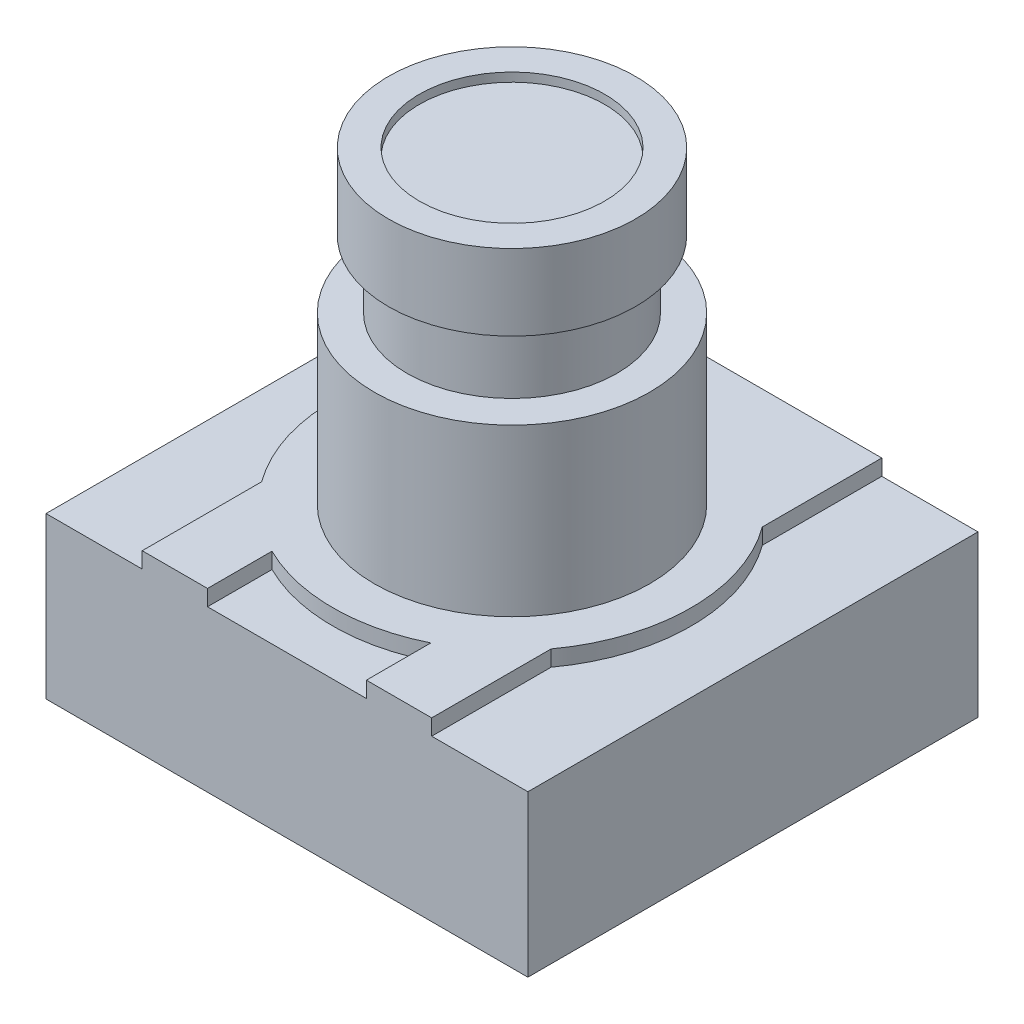
SolidWorks part; units mm, degrees
ref_plane "Front Plane" through (0, 0, 0) normal (0, 0, 1) x (1, 0, 0)
ref_plane "Top Plane" through (0, 0, 0) normal (0, 1, 0) x (1, 0, 0)
ref_plane "Right Plane" through (0, 0, 0) normal (1, 0, 0) x (0, 0, -1)
sketch "Sketch1" plane through (0, 0, 0) normal (0, 1, 0) x (1, 0, 0)
  line L1 (-13.65, 12.75) -> (13.65, 12.75)
  line L2 (-13.65, 12.75) -> (-13.65, -12.75)
  line L3 (-13.65, -12.75) -> (13.65, -12.75)
  line L4 (13.65, 12.75) -> (13.65, -12.75)
  line L5 (-13.65, 12.75) -> (13.65, -12.75) construction
  line L6 (-13.65, -12.75) -> (13.65, 12.75) construction
  point P0 (0, 0)
  dimension "D1" = 27.3
  dimension "D2" = 25.5
extrude "Boss-Extrude1" add sketch "Sketch1" along normal blind 10
sketch "Sketch2" plane through (0, 10, 0) normal (0, 1, 0) x (1, 0, 0)
  line L0 (-8.2, 12.75) -> (-8.2, -12.75)
  line L1 (13.65, 12.75) -> (-13.65, 12.75) construction
  line L2 (-13.65, -12.75) -> (13.65, -12.75) construction
  line L3 (0, 12.75) -> (0, -12.75) construction
  line L4 (8.2, 12.75) -> (8.2, -12.75)
  line L5 (-4.5, -9.0979) -> (-4.5, -12.75)
  line L6 (4.5, -9.0979) -> (4.5, -12.75)
  circle A0 centre (0, 0) radius 10.15
  line M1 (13.65, -12.75) -> (13.65, 12.75)
  line M2 (13.65, 12.75) -> (-13.65, 12.75)
  line M3 (-13.65, 12.75) -> (-13.65, -12.75)
  line M4 (-13.65, -12.75) -> (13.65, -12.75)
  dimension "D1" = 20.3
  dimension "D2" = 16.4
  dimension "D3" = 9
extrude "Cut-Extrude1" cut sketch "Sketch2" against normal blind 0.9 contours A0 L0 M2 M3 M4 | A0 L4 M4 M1 M2 | L3 A0 L5 M4 | A0 L3 L6 M4
sketch "Sketch3" plane through (0, 10, 0) normal (0, 1, 0) x (1, 0, 0)
  circle A0 centre (0, 0) radius 7.8
  dimension "D1" = 15.6
extrude "Boss-Extrude2" add sketch "Sketch3" along normal blind 9.4
sketch "Sketch4" plane through (0, 19.4, 0) normal (0, 1, 0) x (1, 0, 0)
  circle A0 centre (0, 0) radius 5.95
  dimension "D1" = 11.9
extrude "Boss-Extrude3" add sketch "Sketch4" along normal blind 3.8
sketch "Sketch5" plane through (0, 23.2, 0) normal (0, 1, 0) x (1, 0, 0)
  circle A0 centre (0, 0) radius 7
  dimension "D1" = 14
extrude "Boss-Extrude4" add sketch "Sketch5" along normal offset from surface (4.3 mm away) 27.5 up to face at (0, 0, 0)
sketch "Sketch6" plane through (0, 27.5, 0) normal (0, 1, 0) x (1, 0, 0)
  circle A0 centre (0, 0) radius 5.25
  dimension "D1" = 10.5
extrude "Cut-Extrude2" cut sketch "Sketch6" against normal blind 0.5
sketch "Sketch7" plane through (0, 0, 0) normal (0, -1, 0) x (1, 0, 0)
  line L0 (0, 12.75) -> (0, -12.75) construction
  line L1 (-13.65, 12.75) -> (13.65, 12.75) construction
  line L2 (13.65, -12.75) -> (-13.65, -12.75) construction
  line L4 (-3.45, 11.25) -> (3.45, 11.25)
  line L5 (-3.45, 11.25) -> (-3.45, 8.05)
  line L6 (-3.45, 8.05) -> (3.45, 8.05)
  line L7 (3.45, 11.25) -> (3.45, 8.05)
  line L8 (-3.45, 11.25) -> (3.45, 8.05) construction
  line L9 (-3.45, 8.05) -> (3.45, 11.25) construction
  point P6 (0, 9.65)
  dimension "D1" = 6.9
  dimension "D2" = 3.2
  dimension "D3" = 1.5
extrude "Boss-Extrude5" add sketch "Sketch7" along normal blind 1.1
sketch "Sketch8" plane through (0, -1.1, 0) normal (0, -1, 0) x (1, 0, 0)
  line L0 (-3.45, 8.05) -> (3.45, 8.05) construction
  line L1 (-2.95, 8.05) -> (2.95, 8.05)
  line L2 (-2.95, 8.05) -> (-2.95, 10.75)
  line L3 (-2.95, 10.75) -> (2.95, 10.75)
  line L4 (2.95, 8.05) -> (2.95, 10.75)
  line L5 (0, 11.25) -> (0, 8.05) construction
  line L6 (3.45, 11.25) -> (-3.45, 11.25) construction
  line L7 (0, 10.75) -> (0, 8.05) construction
  line L8 (-3.45, 11.25) -> (-3.45, 8.05) construction
  dimension "D1" = 0.5
  dimension "D2" = 0.5
extrude "Cut-Extrude3" cut sketch "Sketch8" against normal blind 2.5
